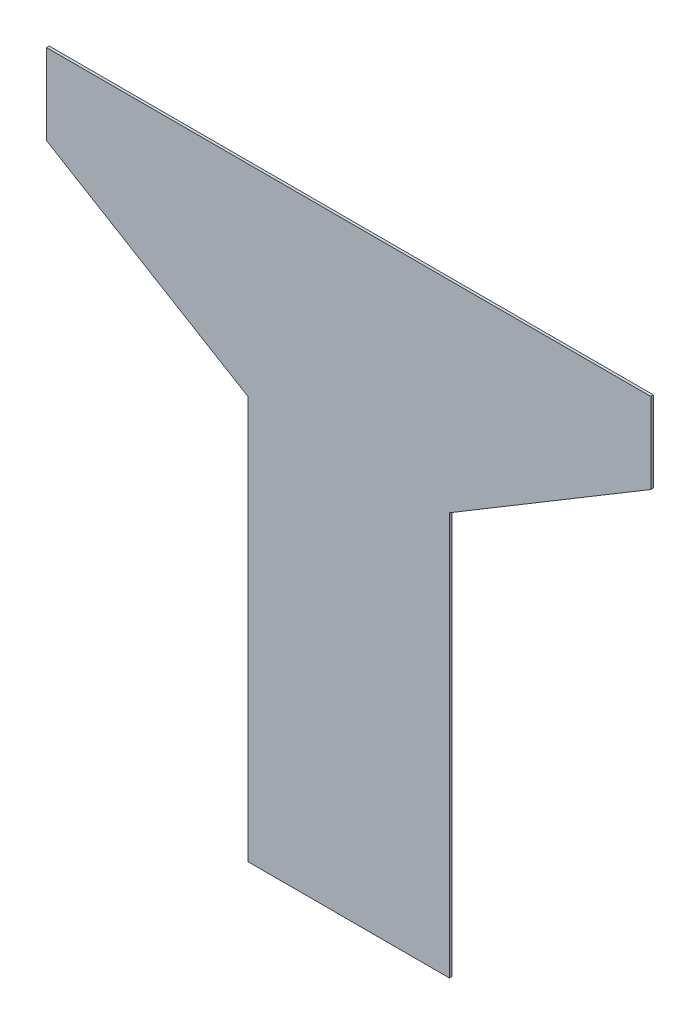
SolidWorks part; units mm, degrees
material "1060 Alloy"
ref_plane "Front Plane" through (0, 0, 0) normal (0, 0, 1) x (1, 0, 0)
ref_plane "Top Plane" through (0, 0, 0) normal (0, 1, 0) x (1, 0, 0)
ref_plane "Right Plane" through (0, 0, 0) normal (1, 0, 0) x (0, 0, -1)
sketch "Sketch1" plane through (0, 0, 0) normal (0, 0, 1) x (1, 0, 0)
  line L0 (75, 0) -> (-75, 0)
  line L1 (-75, 0) -> (-75, -20)
  line L2 (-75, -20) -> (-25, -50)
  line L4 (25, -50) -> (75, -20)
  line L5 (75, -20) -> (75, 0)
  line L6 (-25, -50) -> (-25, -150)
  line L7 (-25, -150) -> (25, -150)
  line L8 (25, -150) -> (25, -50)
  point P4 (0, 0)
  dimension "D1" = 150
  dimension "D2" = 50
  dimension "D3" = 50
  dimension "D4" = 20
  dimension "D5" = 20
extrude "Boss-Extrude1" add sketch "Sketch1" along normal blind 0.6667
scale "Scale1" bodies to scale 101 scale about centroid uniform scaling yes scale factor 3
